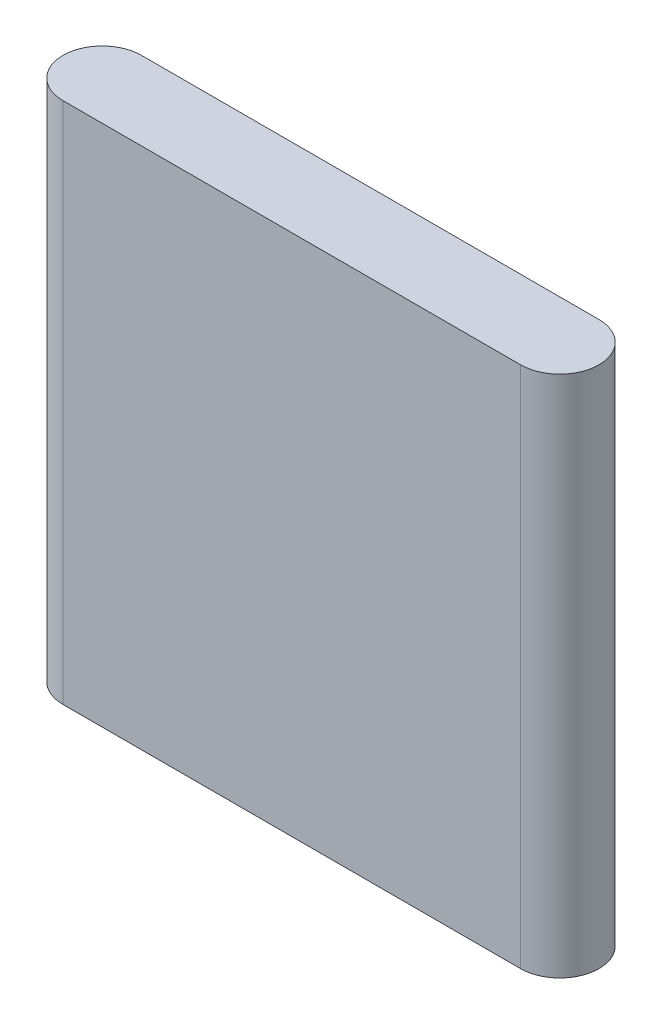
SolidWorks part; units mm, degrees
ref_plane "前视基准面" through (0, 0, 0) normal (0, 0, 1) x (1, 0, 0)
ref_plane "上视基准面" through (0, 0, 0) normal (0, 1, 0) x (1, 0, 0)
ref_plane "右视基准面" through (0, 0, 0) normal (1, 0, 0) x (0, 0, -1)
sketch "草图1" plane through (0, 0, 0) normal (0, 1, 0) x (1, 0, 0)
  line L0 (-17.5, 0) -> (17.5, 0) construction
  line L1 (-17.5, 3) -> (17.5, 3)
  line L2 (-17.5, -3) -> (17.5, -3)
  arc A0 (-17.5, 3) -> (-17.5, -3) centre (-17.5, 0) ccw
  arc A1 (17.5, -3) -> (17.5, 3) centre (17.5, 0) ccw
  point P2 (0, 0)
  dimension "D1" = 3
  dimension "D2" = 35
extrude "凸台-拉伸1" add sketch "草图1" along normal mid plane 40
